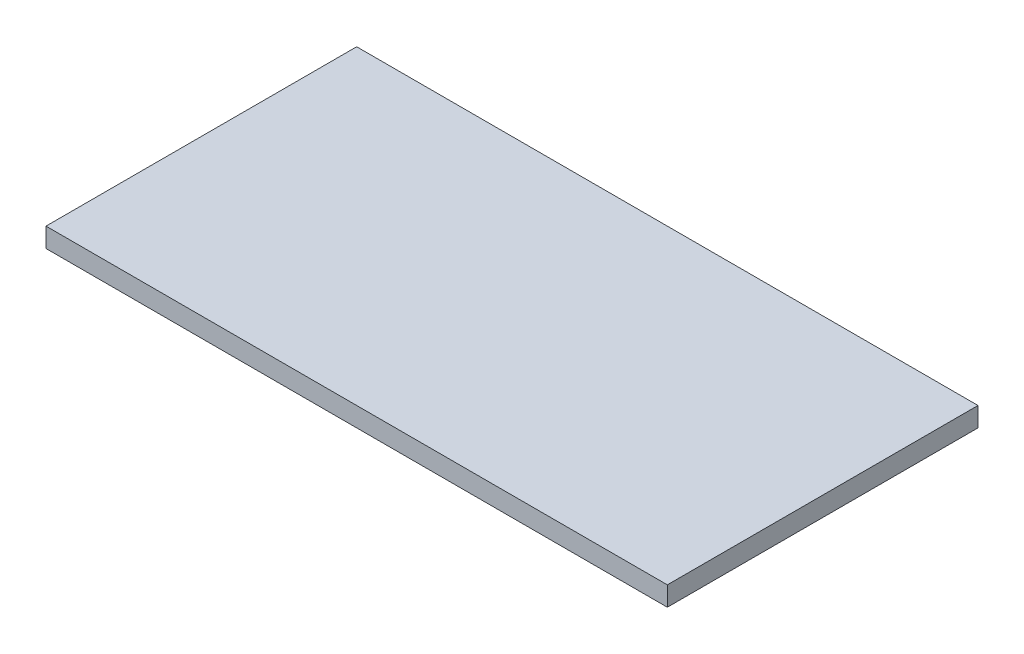
SolidWorks part; units mm, degrees
material "有机玻璃 (TM) GS 丙烯酸铸钣"
ref_plane "前视基准面" through (0, 0, 0) normal (0, 0, 1) x (1, 0, 0)
ref_plane "上视基准面" through (0, 0, 0) normal (0, 1, 0) x (1, 0, 0)
ref_plane "右视基准面" through (0, 0, 0) normal (1, 0, 0) x (0, 0, -1)
other "Configuration Table"
sketch "草图1" plane through (0, 0, 0) normal (0, 1, 0) x (1, 0, 0)
  line L1 (-80, 40) -> (80, 40)
  line L2 (-80, 40) -> (-80, -40)
  line L3 (-80, -40) -> (80, -40)
  line L4 (80, 40) -> (80, -40)
  line L5 (-80, 40) -> (80, -40) construction
  line L6 (-80, -40) -> (80, 40) construction
  point P0 (0, 0)
  dimension "D1" = 160
  dimension "D2" = 80
extrude "凸台-拉伸1" add sketch "草图1" along normal blind 5
